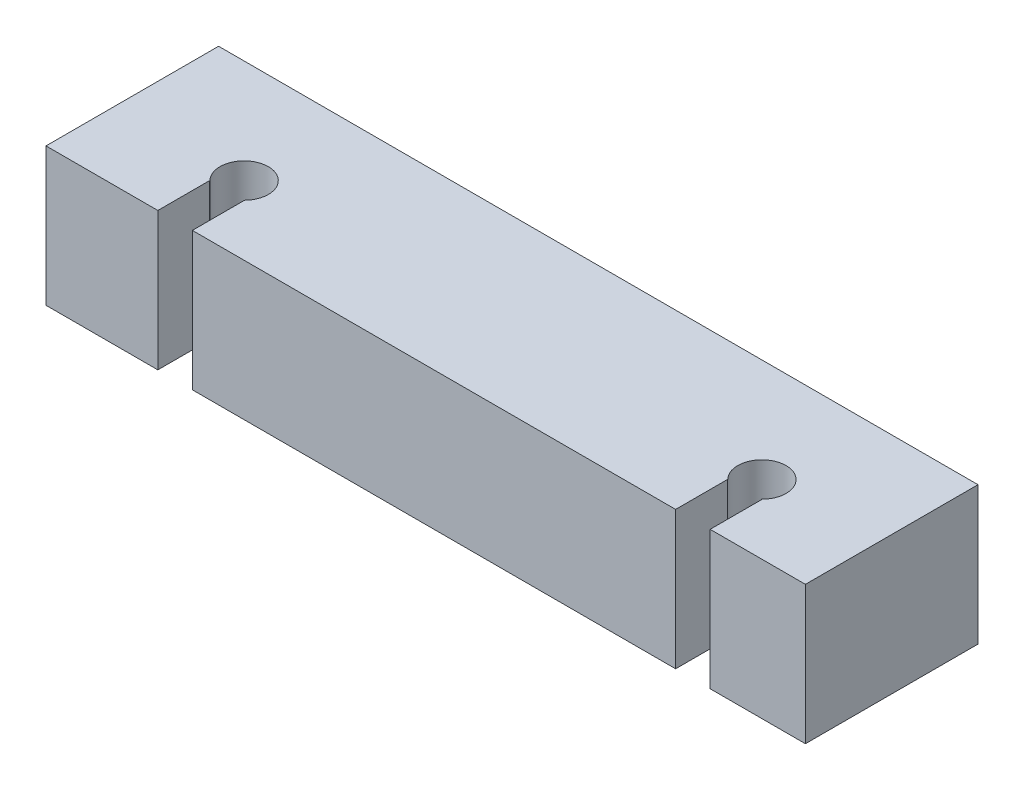
SolidWorks part; units mm, degrees
ref_plane "Front Plane" through (0, 0, 0) normal (0, 0, 1) x (1, 0, 0)
ref_plane "Top Plane" through (0, 0, 0) normal (0, 1, 0) x (1, 0, 0)
ref_plane "Right Plane" through (0, 0, 0) normal (1, 0, 0) x (0, 0, -1)
sketch "Sketch1" plane through (0, 0, 0) normal (0, 1, 0) x (1, 0, 0)
  circle A0 centre (0, 0) radius 62.5
  circle A1 centre (0, 0) radius 72.5
  dimension "D1" = 125
  dimension "D2" = 145
extrude "Boss-Extrude1" add sketch "Sketch1" along normal blind 10
sketch "Sketch2" plane through (0, 0, 0) normal (0, 0, 1) x (1, 0, 0)
  line L0 (72.5, 10) -> (-72.5, 10) construction
  line L1 (-72.5, 0) -> (-47.5, 0)
  line L2 (-72.5, 0) -> (-72.5, 10)
  line L3 (-72.5, 10) -> (-47.5, 10)
  line L4 (-47.5, 0) -> (-47.5, 10)
  line L5 (62.5, 10) -> (-62.5, 10) construction
  line L6 (72.5, 0) -> (47.5, 0)
  line L7 (72.5, 0) -> (72.5, 10)
  line L8 (72.5, 10) -> (47.5, 10)
  line L9 (47.5, 0) -> (47.5, 10)
  point P14 (-47.5, 5)
  dimension "D1" = 25
  dimension "D2" = 25
extrude "Boss-Extrude2" add sketch "Sketch2" along normal blind 100
sketch "Sketch3" plane through (0, 10, 0) normal (0, 1, 0) x (1, 0, 0)
  line L0 (72.5, -100) -> (72.5, 0) construction
  line L1 (-72.5, -100) -> (72.5, -100)
  line L2 (-72.5, -100) -> (-72.5, -50)
  line L3 (-72.5, -50) -> (72.5, -50)
  line L4 (72.5, -100) -> (72.5, -50)
extrude "Boss-Extrude3" add sketch "Sketch3" against normal up to surface (10 mm away) up to face at (0, 0, 6.77)
sketch "Sketch4" plane through (0, 10, 0) normal (0, 1, 0) x (1, 0, 0)
  circle A0 centre (0, 0) radius 62.5
extrude "Cut-Extrude1" cut sketch "Sketch4" against normal up to surface (10 mm away) up to face at (0, 0, 14.9113)
sketch "Sketch5" plane through (0, 10, 0) normal (0, 1, 0) x (1, 0, 0)
  line L0 (72.5, -100) -> (72.5, 0) construction
  line L1 (-72.5, -100) -> (72.5, -100)
  line L2 (-72.5, -100) -> (-72.5, -87.5)
  line L3 (-72.5, -87.5) -> (72.5, -87.5)
  line L4 (72.5, -100) -> (72.5, -87.5)
  dimension "D1" = 12.5
extrude "Boss-Extrude4" add sketch "Sketch5" along normal blind 50
sketch "Sketch6" plane through (0, 0, 0) normal (0, -1, 0) x (1, 0, 0)
  line L0 (-72.5, 100) -> (72.5, 100) construction
  line L1 (-72.5, 100) -> (-72.5, 0) construction
  circle A0 centre (-50.65, 95) radius 1.75
  circle A4 centre (-13.15, 95) radius 1.75
  circle A5 centre (24.35, 95) radius 1.75
  circle A6 centre (61.85, 95) radius 1.75
  dimension "D1" = 4
  dimension "D4" = 3.5
  dimension "D2" = 5
  dimension "D3" = 21.85
extrude "Cut-Extrude2" cut sketch "Sketch6" against normal through all both and the other way through all
sketch "Sketch7" plane through (0, 0, 0) normal (0, -1, 0) x (1, 0, 0)
  line L0 (-50.65, 95) -> (-50.65, 100) construction
  line L1 (-72.5, 100) -> (72.5, 100) construction
  line L2 (-14.4, 96.25) -> (-14.4, 103.75)
  line L3 (-51.9, 96.25) -> (-49.4, 96.25)
  line L4 (-51.9, 96.25) -> (-51.9, 103.75)
  line L5 (-51.9, 103.75) -> (-49.4, 103.75)
  line L6 (-49.4, 96.25) -> (-49.4, 103.75)
  line L7 (-51.9, 96.25) -> (-49.4, 103.75) construction
  line L8 (-51.9, 103.75) -> (-49.4, 96.25) construction
  line L9 (-14.4, 96.25) -> (-11.9, 96.25)
  line L10 (-11.9, 96.25) -> (-11.9, 103.75)
  line L11 (-14.4, 103.75) -> (-11.9, 103.75)
  line L12 (23.1, 96.25) -> (23.1, 103.75)
  line L13 (23.1, 96.25) -> (25.6, 96.25)
  line L14 (25.6, 96.25) -> (25.6, 103.75)
  line L15 (23.1, 103.75) -> (25.6, 103.75)
  line L16 (60.6, 96.25) -> (60.6, 103.75)
  line L17 (60.6, 96.25) -> (63.1, 96.25)
  line L18 (63.1, 96.25) -> (63.1, 103.75)
  line L19 (60.6, 103.75) -> (63.1, 103.75)
  dimension "D1" = 7.5
  dimension "D2" = 2.5
  dimension "D3" = 4
extrude "Cut-Extrude3" cut sketch "Sketch7" against normal through all both and the other way through all
sketch "Sketch8" plane through (0, 60, 0) normal (0, 1, 0) x (1, 0, 0)
  line L1 (-72.5, -100) -> (72.5, -100)
  line L2 (-72.5, -100) -> (-72.5, -87.5)
  line L3 (-72.5, -87.5) -> (72.5, -87.5)
  line L4 (72.5, -100) -> (72.5, -87.5)
extrude "Cut-Extrude4" cut sketch "Sketch8" against normal up to surface (50 mm away) up to face at (0, 10, 25.625)
sketch "Sketch9" plane through (0, 0, 0) normal (0, 0, 1) x (1, 0, 0)
  line L1 (72.5, 0) -> (-72.5, 0)
  line L2 (72.5, 0) -> (72.5, 10)
  line L3 (72.5, 10) -> (-72.5, 10)
  line L4 (-72.5, 0) -> (-72.5, 10)
extrude "Cut-Extrude5" cut sketch "Sketch9" against normal mid plane 175
sketch "Sketch11" plane through (72.5, 0, 0) normal (1, 0, 0) x (0, 0, -1)
  line L1 (-100, 0) -> (-87.5, 0)
  line L2 (-100, 0) -> (-100, 10)
  line L3 (-100, 10) -> (-87.5, 10)
  line L4 (-87.5, 0) -> (-87.5, 10)
extrude "Cut-Extrude7" cut sketch "Sketch11" against normal blind 15
sketch "Sketch13" plane through (-72.5, 0, 0) normal (-1, 0, 0) x (0, 0, 1)
  line L4 (100, 10) -> (87.5, 10)
  line L5 (87.5, 10) -> (87.5, 0)
  line L6 (87.5, 0) -> (100, 0)
  line L7 (100, 0) -> (100, 10)
  line L8 (100, 10) -> (87.5, 10)
  line L9 (87.5, 10) -> (87.5, 0)
  line L10 (87.5, 0) -> (100, 0)
  line L11 (100, 0) -> (100, 10)
  dimension "D1" = 0
extrude "Cut-Extrude9" cut sketch "Sketch13" against normal blind 50
sketch "Sketch14" plane through (57.5, 0, 0) normal (1, 0, 0) x (0, 0, -1)
  line L1 (-87.5, 10) -> (-100, 10)
  line L2 (-87.5, 10) -> (-87.5, 0)
  line L3 (-87.5, 0) -> (-100, 0)
  line L4 (-100, 10) -> (-100, 0)
extrude "Cut-Extrude10" cut sketch "Sketch14" against normal blind 25
